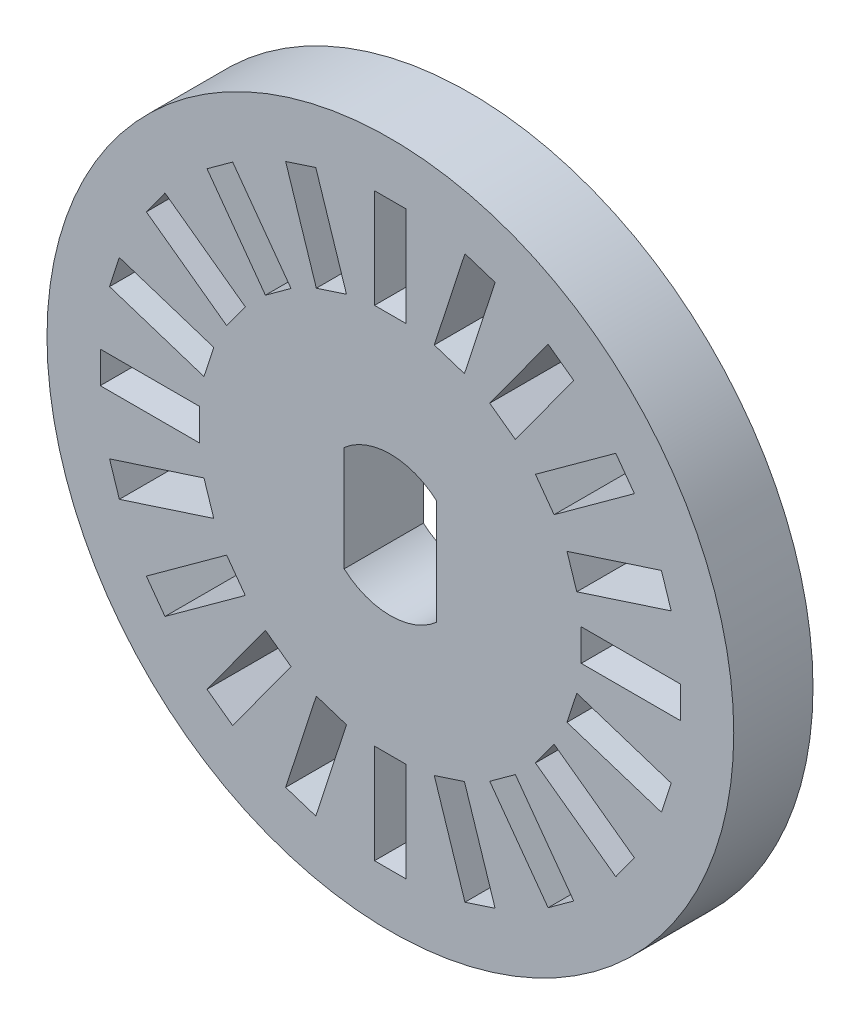
SolidWorks part; units mm, degrees
ref_plane "Front Plane" through (0, 0, 0) normal (0, 0, 1) x (1, 0, 0)
ref_plane "Top Plane" through (0, 0, 0) normal (0, 1, 0) x (1, 0, 0)
ref_plane "Right Plane" through (0, 0, 0) normal (1, 0, 0) x (0, 0, -1)
sketch "Sketch1" plane through (0, 0, 0) normal (0, 0, 1) x (1, 0, 0)
  line L0 (-1.75, 1.99) -> (-1.75, -1.99)
  line L1 (1.75, 1.99) -> (1.75, -1.99)
  circle A0 centre (0, 0) radius 13
  circle A1 centre (0, 0) radius 2.65
  dimension "D1" = 26
  dimension "D2" = 5.3
  dimension "D3" = 3.5
extrude "Boss-Extrude1" add sketch "Sketch1" along normal blind 3 contours A0 A1 | L0 A1 | L1 A1
sketch "Sketch2" plane through (0, 0, 3) normal (0, 0, 1) x (1, 0, 0)
  line L1 (-0.6, 10.9836) -> (0.6, 10.9836)
  line L2 (-0.6, 10.9836) -> (-0.6, 7.2251)
  line L3 (-0.6, 7.2251) -> (0.6, 7.2251)
  line L4 (0.6, 10.9836) -> (0.6, 7.2251)
  circle A0 centre (0, 0) radius 7.25 construction
  circle A1 centre (0, 0) radius 11 construction
  point P8 (0, 7.2251)
  dimension "D1" = 14.5
  dimension "D2" = 22
  dimension "D3" = 1.2
extrude "Cut-Extrude1" cut sketch "Sketch2" against normal through all
pattern_circular "CirPattern1" count 20 over 360 about axis through (0, 0, 0) along (0, 0, 1) of "Cut-Extrude1"
